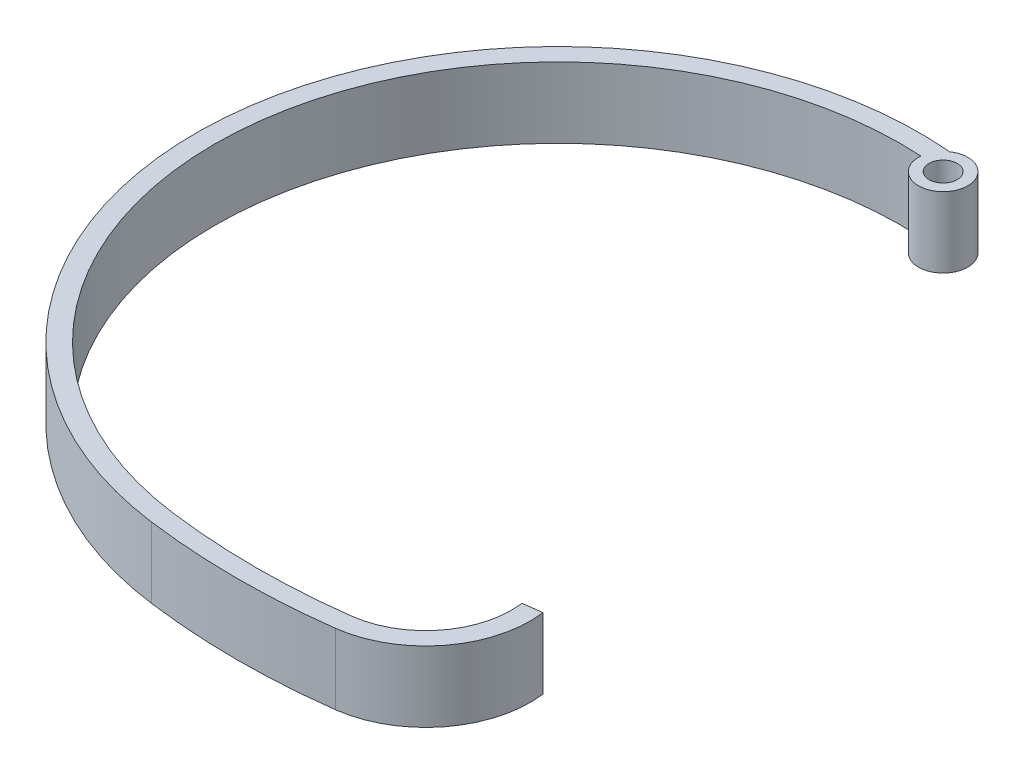
SolidWorks part; units mm, degrees
ref_plane "Plan de face" through (0, 0, 0) normal (0, 0, 1) x (1, 0, 0)
ref_plane "Plan de dessus" through (0, 0, 0) normal (0, 1, 0) x (1, 0, 0)
ref_plane "Plan de droite" through (0, 0, 0) normal (1, 0, 0) x (0, 0, -1)
sketch "Esquisse1" plane through (0, 0, 0) normal (0, 1, 0) x (1, 0, 0)
  line L0 (0, 0) -> (19.0112, -144.757) construction
  line L1 (0, 0) -> (-19.0568, -144.7509) construction
  line L2 (9.5056, -72.3785) -> (19.0112, -144.757) construction
  line L3 (9.5056, -72.3785) -> (19.0112, -144.757) construction
  line L4 (14.2584, -108.5677) -> (19.0112, -144.757) construction
  line L5 (14.2584, -108.5677) -> (19.0112, -144.757) construction
  line L6 (16.6348, -126.6623) -> (34.7294, -124.2859) construction
  line L9 (4.4743, 3.3406) -> (2.8843, -8.7366) construction
  line L10 (0, 0) -> (-1.0815, -8.2145) construction
  line L11 (34.7294, -124.2859) -> (38.6954, -123.7651)
  arc A0 (19.532, -148.7229) -> (38.6954, -123.7651) centre (16.6348, -126.6623) ccw
  arc A1 (19.0112, -144.757) -> (34.7294, -124.2859) centre (16.6348, -126.6623) ccw
  arc A2 (19.0112, -144.757) -> (-19.0568, -144.7509) centre (0, 0) ccw construction
  arc A3 (-19.0568, -144.7509) -> (19.0112, -144.757) centre (0, 0) ccw
  arc A4 (-19.0568, -144.7509) -> (-5.2207, 0.4973) centre (-9.5284, -72.3755) cw
  arc A5 (-19.5789, -148.7167) -> (19.532, -148.7229) centre (0, 0) ccw
  arc A6 (-19.5789, -148.7167) -> (-2.9409, 4.3422) centre (-9.5284, -72.3755) cw
  circle A7 centre (0, 0) radius 3
  arc A8 (-19.5789, -148.7167) -> (4.4743, 3.3406) centre (-9.5284, -72.3755) cw construction
  arc A9 (-5.2207, 0.4973) -> (-2.9409, 4.3422) centre (0, 0) ccw
  arc A11 (-19.0568, -144.7509) -> (0, 0) centre (-9.5284, -72.3755) cw construction
  dimension "D1" = 4
extrude "Boss.-Extru.3" add sketch "Esquisse1" along normal blind 15
hole_wizard "Trou taraudé M3x0.51" positions "Esquisse8" profile "Esquisse7" tap size "M3x0.5" standard "Ansi Métrique"
sketch "Esquisse8" plane through (0, 0, 0) normal (0, 0, 1) x (1, 0, 0)
  line L0 (19.532, 15) -> (-19.5789, 15) construction
  line L1 (-3, 15) -> (-3, 0) construction
  point P0 (0, 7.5)
  point P2 (-0.0234, 15)
  dimension "D1" = 7.5
  dimension "D2" = 3
sketch "Esquisse7" plane through (0, 7.5, 0) normal (1, 0, 0) x (0, -1, 0)
  line L0 (0, 0) -> (0, 5.2444)
  line L1 (0, 5.2444) -> (1.25, 5.2444)
  line L2 (1.25, 5.2444) -> (1.25, 0)
  line L5 (1.25, 0) -> (0, 0)
  line L11 (0, -6.35) -> (0, 107.95) construction
  dimension "Diamètre du trou pour taraudage jusqu'au prochain" = 2.5
  dimension "Profondeur du trou pour taraudage jusqu'au prochain" = 5.2444
cosmetic thread "Filetage de perçage1" parameters "D1"=0, "D2"=3.5
